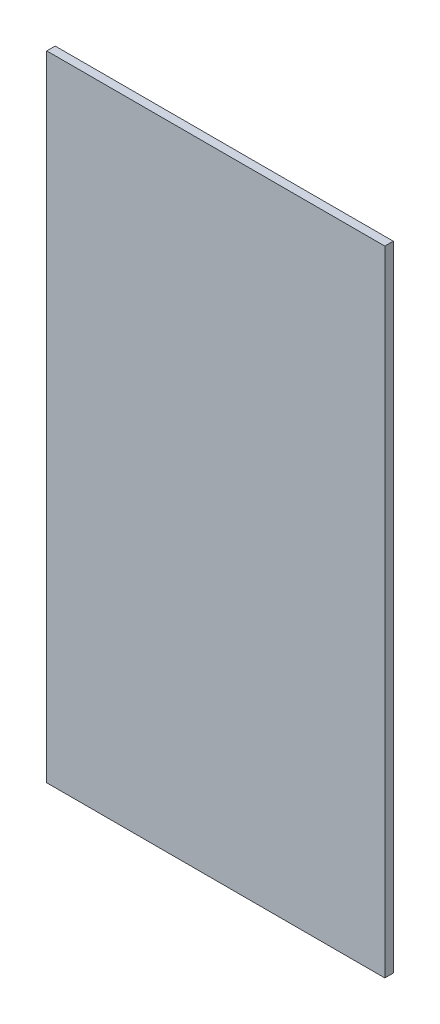
SolidWorks part; units mm, degrees
ref_plane "Front Plane" through (0, 0, 0) normal (0, 0, 1) x (1, 0, 0)
ref_plane "Top Plane" through (0, 0, 0) normal (0, 1, 0) x (1, 0, 0)
ref_plane "Right Plane" through (0, 0, 0) normal (1, 0, 0) x (0, 0, -1)
sketch "Sketch1" plane through (0, 0, 0) normal (0, 0, 1) x (1, 0, 0)
  line L1 (0, 0) -> (400, 0)
  line L2 (0, 0) -> (0, -750)
  line L3 (0, -750) -> (400, -750)
  line L4 (400, 0) -> (400, -750)
  dimension "D1" = 750
  dimension "D2" = 400
extrude "Boss-Extrude1" add sketch "Sketch1" along normal blind 10
sketch "Sketch2" plane through (400, 0, 0) normal (1, 0, 0) x (0, 0, -1)
  line L0 (0, 0) -> (-10, 0)
  line L1 (0, -200) -> (-10, -200)
  line L2 (0, -750) -> (0, 0) construction
  line L3 (-10, -750) -> (-10, 0) construction
  dimension "D1" = 200
